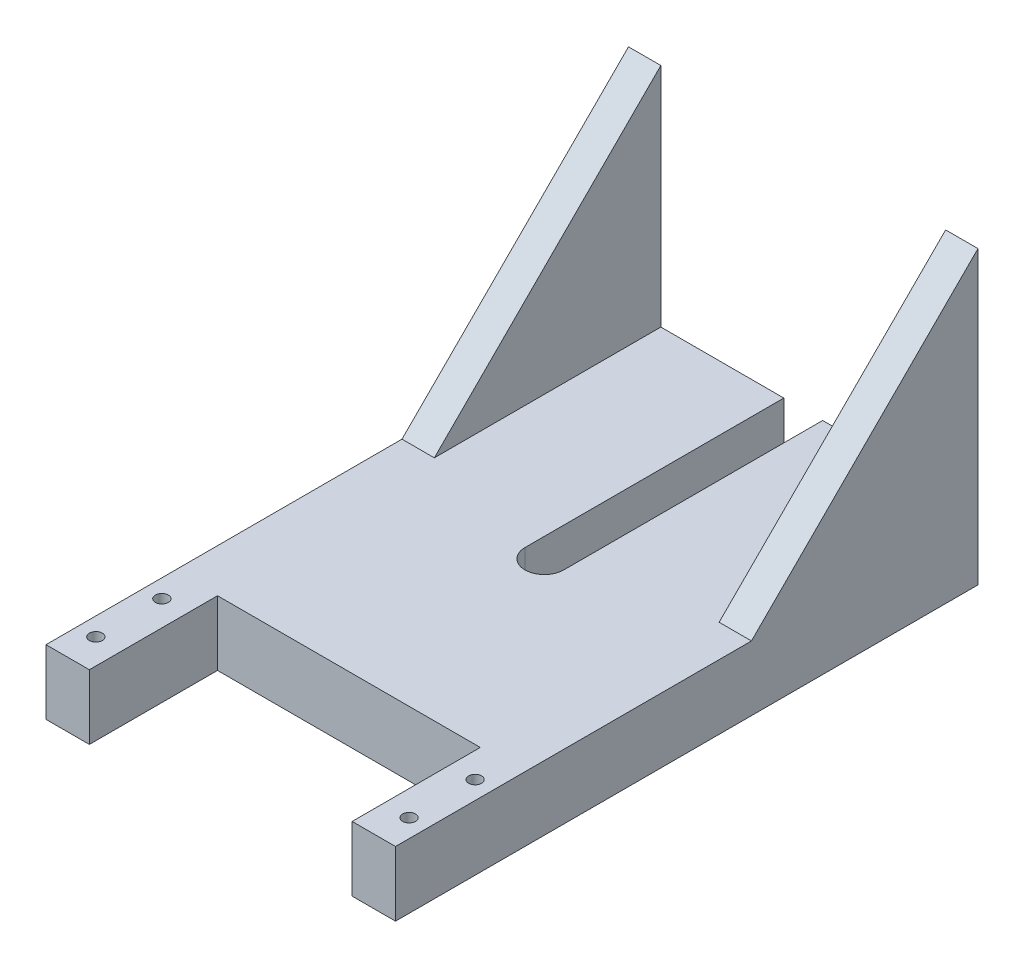
SolidWorks part; units mm, degrees
ref_plane "Front Plane" through (0, 0, 0) normal (0, 0, 1) x (1, 0, 0)
ref_plane "Top Plane" through (0, 0, 0) normal (0, 1, 0) x (1, 0, 0)
ref_plane "Right Plane" through (0, 0, 0) normal (1, 0, 0) x (0, 0, -1)
sketch "Sketch1" plane through (0, 0, 0) normal (0, 0, 1) x (1, 0, 0)
  line L0 (-16.0284, 532.1756) -> (37.9716, 532.1756)
  line L1 (-16.0284, 532.1756) -> (-16.0284, 522.1756)
  line L2 (-16.0284, 522.1756) -> (37.9716, 522.1756)
  line L3 (37.9716, 532.1756) -> (37.9716, 522.1756)
  dimension "D1" = 54
  dimension "D2" = 10
extrude "Boss-Extrude1" add sketch "Sketch1" along normal blind 90 contours L0 L3 L2 L1
sketch "Sketch2" plane through (0, 522.1756, 0) normal (0, -1, 0) x (1, 0, 0)
  line L0 (-16.0284, 90) -> (37.9716, 90) construction
  line L1 (-9.3284, 90) -> (31.2716, 90)
  line L2 (-9.3284, 90) -> (-9.3284, 70.2)
  line L3 (-9.3284, 70.2) -> (31.2716, 70.2)
  line L4 (31.2716, 90) -> (31.2716, 70.2)
  line L5 (10.9716, 70.2) -> (10.9716, 0) construction
  line L7 (-16.0284, 0) -> (37.9716, 0) construction
  point P10 (0, 0)
  point P11 (0, 0)
  dimension "D1" = 40.6
  dimension "D2" = 19.8
extrude "Cut-Extrude1" cut sketch "Sketch2" against normal through all
sketch "Sketch4" plane through (0, 532.1756, 0) normal (0, 1, 0) x (1, 0, 0)
  line L0 (10.9716, -70.2) -> (10.9716, 0) construction
  line L1 (-9.3284, -70.2) -> (31.2716, -70.2) construction
  line L2 (-16.0284, 0) -> (37.9716, 0) construction
  line L3 (10.9716, -40) -> (10.9716, 0) construction
  line L4 (7.9716, -40) -> (7.9716, 0)
  line L5 (13.9716, -40) -> (13.9716, 0)
  arc A0 (7.9716, -40) -> (13.9716, -40) centre (10.9716, -40) ccw
  arc A1 (13.9716, 0) -> (7.9716, 0) centre (10.9716, 0) ccw
  point P7 (10.9716, -20)
extrude "Cut-Extrude2" cut sketch "Sketch4" against normal through all
sketch "Sketch7" plane through (-16.0284, 0, 0) normal (-1, 0, 0) x (0, 0, 1)
  line L0 (35, 532.1756) -> (0, 567.1756)
  line L1 (90, 532.1756) -> (0, 532.1756) construction
  line L2 (0, 654.6756) -> (0, 354.6756) construction
  line L3 (0, 567.1756) -> (0, 532.1756)
  line L4 (0, 532.1756) -> (35, 532.1756)
extrude "Boss-Extrude4" add sketch "Sketch7" against normal blind 5
sketch "Sketch8" plane through (37.9716, 0, 0) normal (1, 0, 0) x (0, 0, -1)
  line L0 (-35, 532.1756) -> (0, 567.1756)
  line L1 (0, 567.1756) -> (0, 532.1756)
  line L2 (0, 532.1756) -> (-35, 532.1756)
extrude "Boss-Extrude5" add sketch "Sketch8" against normal blind 5
sketch "Sketch9" plane through (0, 522.1756, 0) normal (0, -1, 0) x (1, 0, 0)
  line L0 (-13.2284, 85.1) -> (35.1716, 85.1) construction
  line L3 (-13.2284, 74.9) -> (35.1716, 74.9) construction
  line L6 (-13.2284, 85.1) -> (-13.2284, 74.9) construction
  line L7 (35.1716, 74.9) -> (35.1716, 85.1) construction
  circle A0 centre (-13.2284, 85.1) radius 1
  circle A1 centre (-13.2284, 74.9) radius 1
  circle A2 centre (35.1716, 74.9) radius 1
  circle A3 centre (35.1716, 85.1) radius 1
extrude "Cut-Extrude3" cut sketch "Sketch9" against normal through all
